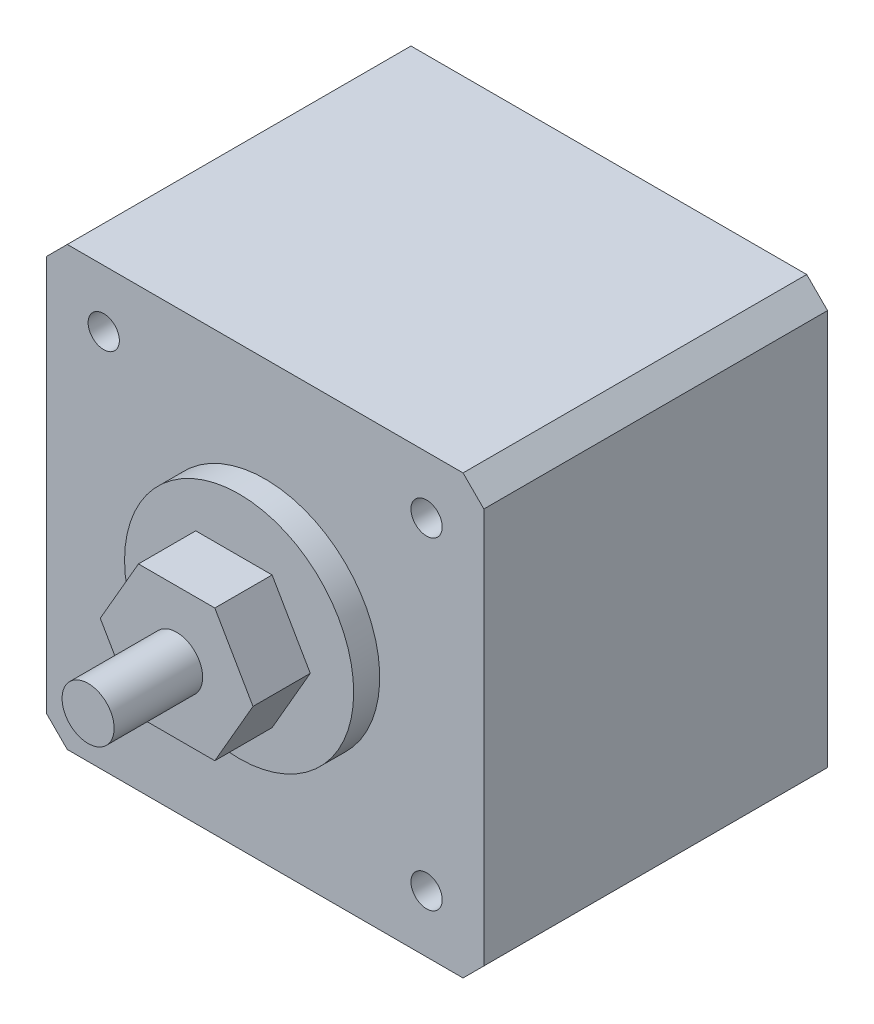
SolidWorks part; units mm, degrees
ref_plane "Front Plane" through (0, 0, 0) normal (0, 0, 1) x (1, 0, 0)
ref_plane "Top Plane" through (0, 0, 0) normal (0, 1, 0) x (1, 0, 0)
ref_plane "Right Plane" through (0, 0, 0) normal (1, 0, 0) x (0, 0, -1)
sketch "Sketch1" plane through (0, 0, 0) normal (0, 0, 1) x (1, 0, 0)
  line L0 (-21, 19) -> (-19, 21)
  line L1 (-19, 21) -> (19, 21)
  line L2 (-21, 19) -> (-21, -19)
  line L3 (-19, -21) -> (19, -21)
  line L4 (21, 19) -> (21, -19)
  line L5 (-21, 21) -> (21, -21) construction
  line L6 (-21, -21) -> (21, 21) construction
  line L7 (19, 21) -> (21, 19)
  line L8 (21, -19) -> (19, -21)
  line L9 (-21, -19) -> (-19, -21)
  point P0 (0, 0)
  dimension "D4" = 2
  dimension "D5" = 2
  dimension "D6" = 2
  dimension "D7" = 2
extrude "Extrude1" add sketch "Sketch1" along normal blind 33
sketch "Sketch2" plane through (0, 0, 33) normal (0, 0, 1) x (1, 0, 0)
  circle A0 centre (-15.5, 15.5) radius 1.5
  circle A1 centre (15.5, 15.5) radius 1.5
  circle A2 centre (-15.5, -15.5) radius 1.5
  circle A3 centre (15.5, -15.5) radius 1.5
  point P0 (0, 0)
extrude "Extrude2" cut sketch "Sketch2" against normal blind 43
sketch "Sketch3" plane through (0, 0, 33) normal (0, 0, 1) x (1, 0, 0)
  circle A0 centre (0, 0) radius 11
extrude "Extrude3" add sketch "Sketch3" along normal blind 2.5
sketch "Sketch4" plane through (0, 0, 35.5) normal (0, 0, 1) x (1, 0, 0)
  circle A0 centre (0, 0) radius 2.5
extrude "Extrude4" add sketch "Sketch4" along normal blind 14.5 and the other way blind 37
sketch "Sketch5" plane through (0, 0, 35.5) normal (0, 0, 1) x (1, 0, 0)
  line L1 (7.3323, 0) -> (3.6662, 6.35)
  line L2 (3.6662, 6.35) -> (-3.6662, 6.35)
  line L3 (-3.6662, 6.35) -> (-7.3323, 0)
  line L4 (-7.3323, 0) -> (-3.6662, -6.35)
  line L5 (-3.6662, -6.35) -> (3.6662, -6.35)
  line L6 (3.6662, -6.35) -> (7.3323, 0)
  circle A1 centre (0, 0) radius 6.35 construction
extrude "Boss-Extrude1" add sketch "Sketch5" along normal blind 5.5 from offset 0.5
